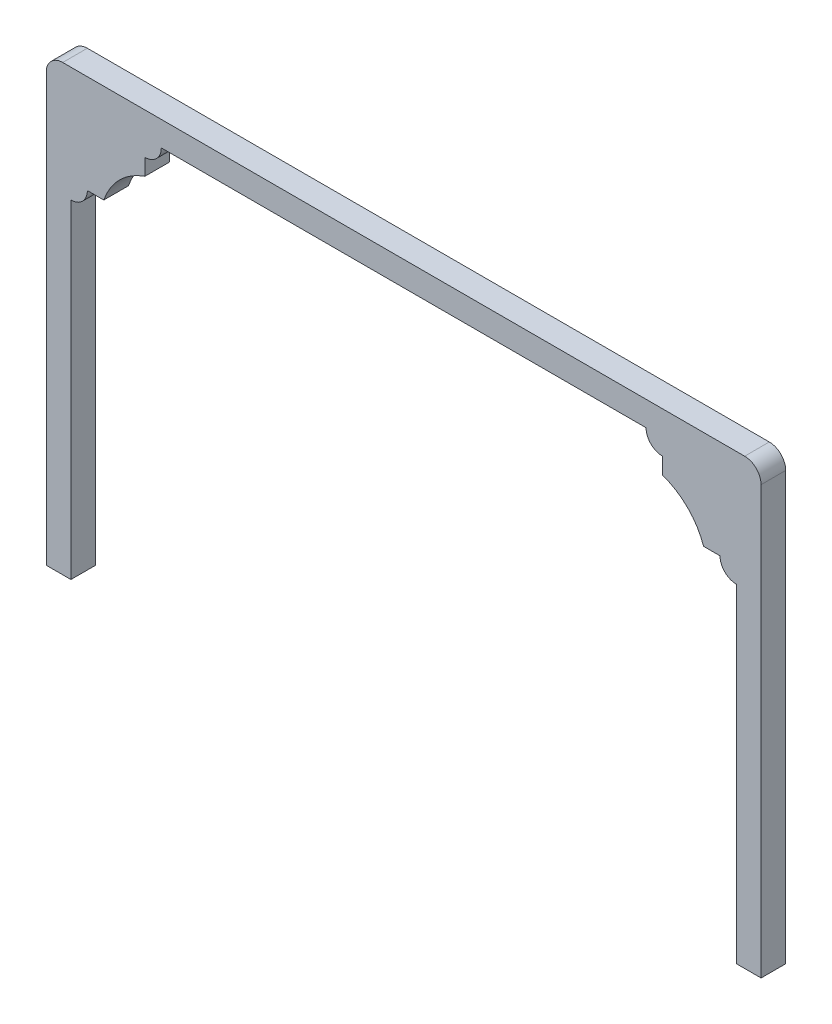
SolidWorks part; units mm, degrees
material "Pine"
ref_plane "Front Plane" through (0, 0, 0) normal (0, 0, 1) x (1, 0, 0)
ref_plane "Top Plane" through (0, 0, 0) normal (0, 1, 0) x (1, 0, 0)
ref_plane "Right Plane" through (0, 0, 0) normal (1, 0, 0) x (0, 0, -1)
sketch "Sketch1" plane through (0, 0, 0) normal (0, 0, 1) x (1, 0, 0)
  line L0 (276.225, 0) -> (276.225, 342.9) construction
  line L1 (276.225, 0) -> (257.175, 0)
  line L2 (257.175, 0) -> (257.175, 76.2)
  line L3 (276.225, 342.9) -> (-276.225, 342.9) construction
  line L5 (257.175, 76.2) -> (257.175, 165.1) construction
  line L7 (0, 342.9) -> (0, 0) construction
  line L8 (0, 76.2) -> (276.225, 76.2) construction
  line L11 (276.225, 0) -> (276.225, 330.2)
  line L12 (257.175, 165.1) -> (257.175, 76.2)
  line L20 (257.175, 165.1) -> (257.175, 254)
  line L21 (263.525, 342.9) -> (-263.525, 342.9)
  line L24 (-187.325, 323.85) -> (187.325, 323.85)
  line L26 (276.225, 323.85) -> (200.025, 323.85) construction
  line L27 (200.025, 311.15) -> (200.025, 298.45)
  line L30 (244.475, 266.7) -> (231.775, 266.7)
  line L31 (257.175, 323.85) -> (276.225, 342.9) construction
  line L32 (238.125, 342.9) -> (276.225, 304.8) construction
  line L34 (257.175, 323.85) -> (183.6773, 250.3523) construction
  line L35 (200.025, 298.45) -> (200.025, 266.7) construction
  line L36 (200.025, 266.7) -> (231.775, 266.7) construction
  line L37 (187.325, 323.85) -> (0, 323.85) construction
  line L38 (257.175, 254) -> (257.175, 266.7) construction
  line L39 (200.025, 323.85) -> (187.325, 323.85) construction
  line L40 (257.175, 266.7) -> (257.175, 323.85) construction
  line L42 (200.025, 323.85) -> (200.025, 311.15) construction
  line L43 (-276.225, 0) -> (-276.225, 330.2)
  line L44 (-276.225, 0) -> (-257.175, 0)
  line L45 (-257.175, 0) -> (-257.175, 76.2)
  line L46 (-257.175, 165.1) -> (-257.175, 76.2)
  line L47 (-257.175, 165.1) -> (-257.175, 254)
  line L48 (-244.475, 266.7) -> (-231.775, 266.7)
  line L49 (-200.025, 311.15) -> (-200.025, 298.45)
  arc A1 (231.775, 266.7) -> (200.025, 298.45) centre (183.6773, 250.3523) ccw
  arc A3 (200.025, 311.15) -> (187.325, 323.85) centre (200.025, 323.85) cw
  arc A4 (257.175, 254) -> (244.475, 266.7) centre (257.175, 266.7) cw
  arc A5 (263.525, 342.9) -> (276.225, 330.2) centre (263.525, 330.2) cw
  arc A7 (-263.525, 342.9) -> (-276.225, 330.2) centre (-263.525, 330.2) ccw
  arc A8 (-257.175, 254) -> (-244.475, 266.7) centre (-257.175, 266.7) ccw
  arc A9 (-231.775, 266.7) -> (-200.025, 298.45) centre (-183.6773, 250.3523) cw
  arc A10 (-200.025, 311.15) -> (-187.325, 323.85) centre (-200.025, 323.85) ccw
  point P7 (257.175, 323.85)
  point P16 (0, 342.9)
  point P21 (227.6196, 294.2946)
  point P39 (228.6978, 323.85)
  point P40 (226.442, 305.5809)
  point P41 (222.5659, 308.5104)
  point P59 (222.3208, 316.4747)
  point P60 (222.4908, 308.5391)
  point P61 (222.1292, 316.6031)
  point P62 (0, 0)
  point P63 (222.1867, 308.6658)
  point P64 (221.8129, 316.8105)
  point P65 (220.7663, 317.4792)
  point P66 (220.6904, 309.542)
  dimension "D6" = 12.7
  dimension "D8" = 12.7
  dimension "D9" = 88.9
  dimension "D10" = 50.8
  dimension "D11" = 12.7
  dimension "D1" = 342.9
  dimension "D2" = 19.05
  dimension "D3" = 552.45
  dimension "D4" = 76.2
  dimension "D5" = 19.05
  dimension "D7" = 88.9
extrude "Boss-Extrude1" add sketch "Sketch1" along normal blind 19.05
